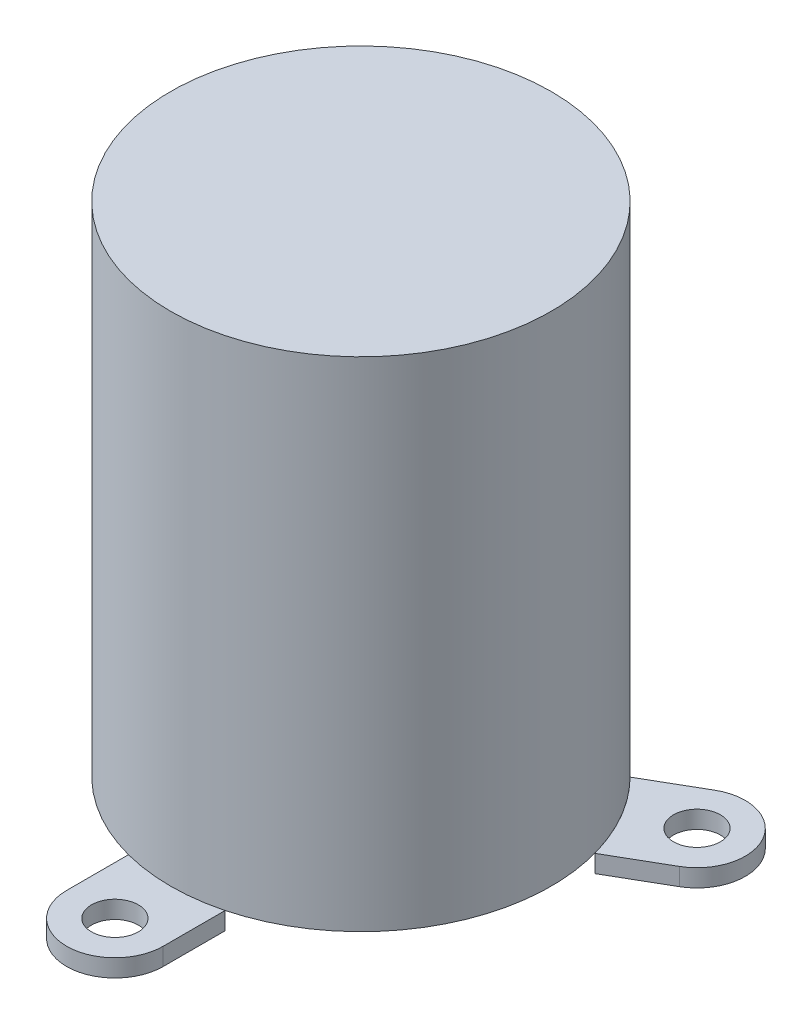
SolidWorks part; units mm, degrees
ref_plane "Ebene vorne" through (0, 0, 0) normal (0, 0, 1) x (1, 0, 0)
ref_plane "Ebene oben" through (0, 0, 0) normal (0, 1, 0) x (1, 0, 0)
ref_plane "Ebene rechts" through (0, 0, 0) normal (1, 0, 0) x (0, 0, -1)
sketch "Sketch1" plane through (0, 0, 0) normal (0, 1, 0) x (1, 0, 0)
  circle A0 centre (0, 0) radius 6.5
  dimension "D1" = 13
extrude "Boss-Extrude1" add sketch "Sketch1" along normal blind 17
sketch "Sketch2" plane through (0, 0, 0) normal (0, -1, 0) x (-1, 0, 0)
  line L0 (1.65, -6.2871) -> (1.65, -8.4)
  line L1 (-1.65, -6.2871) -> (-1.65, -8.4)
  line L2 (0, 0) -> (0, -15.0921) construction
  line L3 (-6.2698, 1.7146) -> (-8.0996, 2.7711)
  line L4 (-4.6198, 4.5725) -> (-6.4496, 5.6289)
  line L5 (4.6198, 4.5725) -> (6.4496, 5.6289)
  line L6 (6.2698, 1.7146) -> (8.0996, 2.7711)
  circle A0 centre (0, 0) radius 6.5 construction
  arc A1 (1.65, -8.4) -> (-1.65, -8.4) centre (0, -8.4) cw
  circle A2 centre (0, -8.4) radius 0.8
  arc A3 (1.65, -6.2871) -> (-1.65, -6.2871) centre (0, 0) cw
  arc A4 (-8.0996, 2.7711) -> (-6.4496, 5.6289) centre (-7.2746, 4.2) cw
  arc A5 (-6.2698, 1.7146) -> (-4.6198, 4.5725) centre (0, 0) cw
  circle A6 centre (-7.2746, 4.2) radius 0.8
  arc A7 (6.4496, 5.6289) -> (8.0996, 2.7711) centre (7.2746, 4.2) cw
  arc A8 (4.6198, 4.5725) -> (6.2698, 1.7146) centre (0, 0) cw
  circle A9 centre (7.2746, 4.2) radius 0.8
  point P27 (0, 0)
  dimension "D2" = 8.4
  dimension "D3" = 1.6
  dimension "D1" = 3.3
  dimension "D4" = 3
extrude "Boss-Extrude2" add sketch "Sketch2" along normal blind 0.6 separate body
